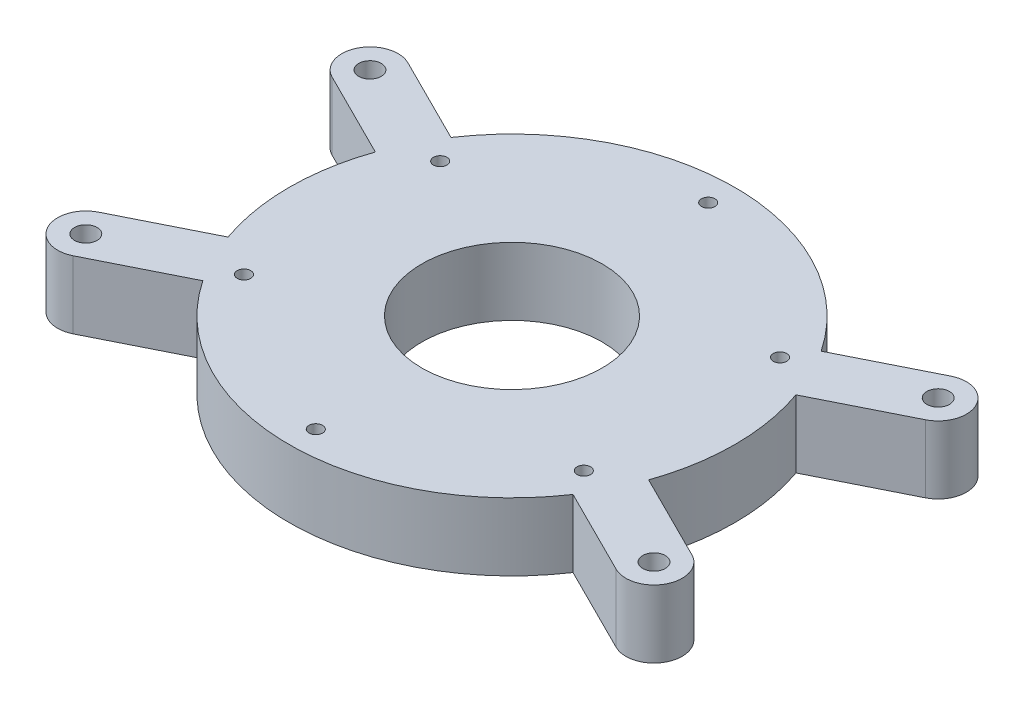
SolidWorks part; units mm, degrees
ref_plane "前视基准面" through (0, 0, 0) normal (0, 0, 1) x (1, 0, 0)
ref_plane "上视基准面" through (0, 0, 0) normal (0, 1, 0) x (1, 0, 0)
ref_plane "右视基准面" through (0, 0, 0) normal (1, 0, 0) x (0, 0, -1)
sketch "草图1" plane through (0, 0, 0) normal (0, 1, 0) x (1, 0, 0)
  line L0 (65.782, 25.9101) -> (46.6233, 16.3287)
  line L1 (60.1908, 37.0899) -> (41.0322, 27.5085)
  line L2 (0, 135.0816) -> (0, -134.5462) construction
  line L3 (161.8892, 80.9621) -> (-87.1466, -43.5827) construction
  line L7 (-65.782, 25.9101) -> (-46.6233, 16.3287)
  line L8 (-50, 21.5) -> (50, 21.5) construction
  line L9 (-50, 21.5) -> (-50, -21.5) construction
  line L10 (-50, -21.5) -> (50, -21.5) construction
  line L11 (50, 21.5) -> (50, -21.5) construction
  line L12 (-60.1908, 37.0899) -> (-41.0322, 27.5085)
  line L13 (-133.256, 0) -> (145.6129, 0) construction
  line L14 (65.782, -25.9101) -> (46.6233, -16.3287)
  line L15 (60.1908, -37.0899) -> (41.0322, -27.5085)
  line L16 (-65.782, -25.9101) -> (-46.6233, -16.3287)
  line L17 (-60.1908, -37.0899) -> (-41.0322, -27.5085)
  circle A0 centre (0, 0) radius 20
  circle A1 centre (0, 0) radius 49.4
  circle A2 centre (62.9864, 31.5) radius 6.25
  circle A6 centre (-62.9864, 31.5) radius 6.25
  circle A7 centre (62.9864, -31.5) radius 6.25
  circle A8 centre (-62.9864, -31.5) radius 6.25
  point P19 (0, 21.5)
  point P20 (50, 0)
  point P41 (0, 0)
  dimension "D2" = 12.5
  dimension "D5" = 98.8
  dimension "D7" = 40
  dimension "D1" = 63.43
  dimension "D3" = 100
  dimension "D4" = 43
  dimension "D6" = 10
extrude "凸台-拉伸1" add sketch "草图1" along normal blind 15 contours A1 A0 | L12 A6 L7 A1 | A8 L17 A1 L16 | A8 | L15 A7 L14 A1 | A7 | A2 | A2 L1 A1 L0
sketch "草图2" plane through (0, 15, 0) normal (0, 1, 0) x (1, 0, 0)
  line L0 (0, 78.1952) -> (0, -57.2274) construction
  line L1 (-93.9988, 0) -> (82.0699, 0) construction
  circle A0 centre (-62.9864, 31.5) radius 2.5
  arc A1 (-60.1908, 37.0899) -> (-65.782, 25.9101) centre (-62.9864, 31.5) ccw construction
  dimension "D1" = 5
extrude "切除-拉伸1" cut sketch "草图2" against normal blind 10
cosmetic thread "装饰螺纹线6" parameters "D1"=5, "D2"=6
mirror "镜向1" about plane through (0, 0, 0) normal (0, 0, 1) of "切除-拉伸1"
cosmetic thread "装饰螺纹线7" parameters "D1"=5, "D2"=6
mirror "镜向2" about plane through (0, 0, 0) normal (1, 0, 0) of "镜向1", "切除-拉伸1"
cosmetic thread "装饰螺纹线8" parameters "D1"=5, "D2"=6
cosmetic thread "装饰螺纹线9" parameters "D1"=5, "D2"=6
ref_plane "基准面1" through (0, 7.5, 0) normal (0, -1, 0) x (-1, 0, 0)
sketch "草图3" plane through (0, 0, 0) normal (0, -1, 0) x (1, 0, 0)
  line L1 (-65.782, 25.9101) -> (-46.6233, 16.3287) construction
  circle A0 centre (-54.0425, 27.0271) radius 2.5
  circle A2 centre (-62.9864, 31.5) radius 2.0501 construction
  arc A3 (-60.1908, 37.0899) -> (-65.782, 25.9101) centre (-62.9864, 31.5) ccw construction
  dimension "D1" = 5
  dimension "D3" = 10
  dimension "D2" = 6.25
extrude "切除-拉伸2" cut sketch "草图3" against normal blind 10
cosmetic thread "装饰螺纹线5" parameters "D2"=6
mirror "镜向3" about plane through (0, 0, 0) normal (1, 0, 0) of "切除-拉伸2"
cosmetic thread "装饰螺纹线10" parameters "D2"=6
mirror "镜向4" about plane through (0, 0, 0) normal (0, 0, 1) of "镜向3", "切除-拉伸2"
cosmetic thread "装饰螺纹线11" parameters "D2"=6
cosmetic thread "装饰螺纹线12" parameters "D2"=6
sketch "草图4" plane through (0, 0, 0) normal (0, -1, 0) x (1, 0, 0)
  circle A0 centre (0, -43.5) radius 1.5
  dimension "D1" = 3
  dimension "D2" = 43.5
extrude "切除-拉伸3" cut sketch "草图4" against normal through all
cosmetic thread "装饰螺纹线13" parameters "D2"=4
pattern_circular "阵列(圆周)1" count 6 over 360 about axis through (0, 0, 0) along (0, 1, 0) of "切除-拉伸3"
cosmetic thread "装饰螺纹线14" parameters "D2"=4
cosmetic thread "装饰螺纹线15" parameters "D2"=4
cosmetic thread "装饰螺纹线16" parameters "D2"=4
cosmetic thread "装饰螺纹线17" parameters "D2"=4
cosmetic thread "装饰螺纹线18" parameters "D2"=4
